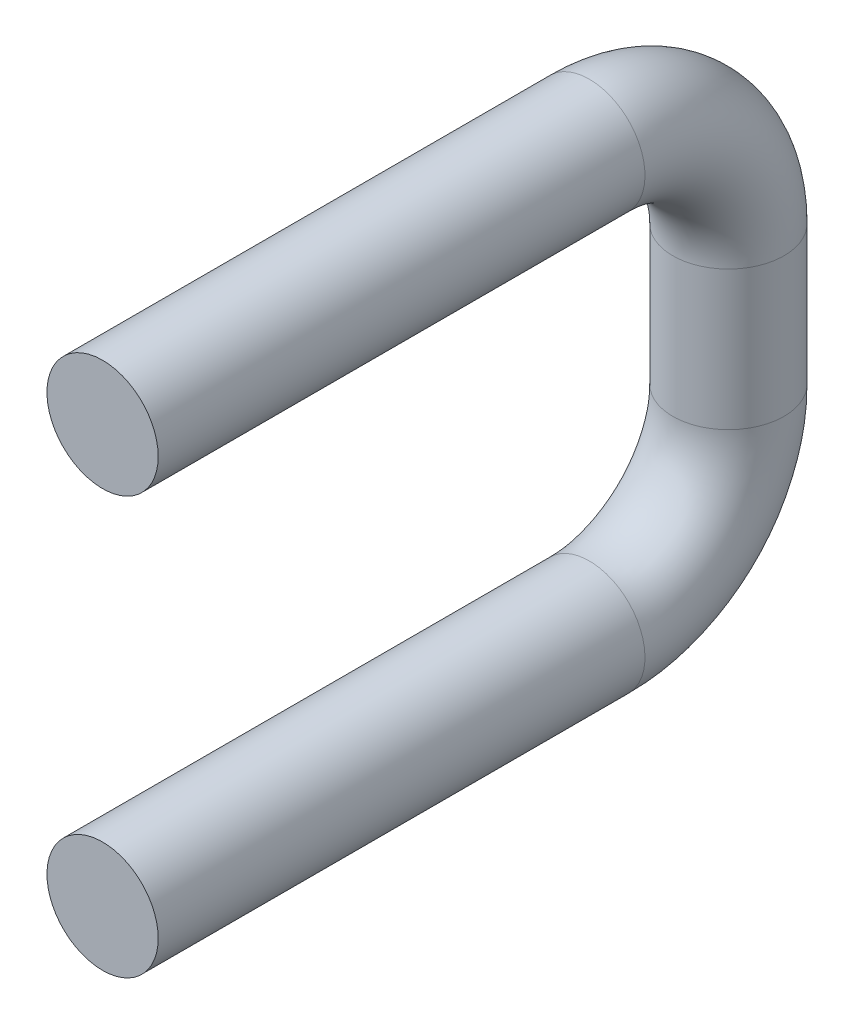
SolidWorks part; units mm, degrees
material "СТ3КП"
ref_plane "Спереди" through (0, 0, 0) normal (0, 0, 1) x (1, 0, 0)
ref_plane "Сверху" through (0, 0, 0) normal (0, 1, 0) x (1, 0, 0)
ref_plane "Справа" through (0, 0, 0) normal (1, 0, 0) x (0, 0, -1)
sketch "Эскиз1" plane through (0, 0, 0) normal (1, 0, 0) x (0, 0, -1)
  line L0 (-15, 15) -> (-15, -15) construction
  line L3 (0, -15) -> (35, -15)
  line L4 (45, 5) -> (45, -5)
  line L5 (-15, -15) -> (15, 15) construction
  line L6 (15, 15) -> (15, -15) construction
  line L7 (0, -1000) -> (0, 49000) construction
  line L8 (0, 15) -> (35, 15)
  arc A0 (35, 15) -> (45, 5) centre (35, 5) cw
  arc A1 (35, -15) -> (45, -5) centre (35, -5) ccw
  point P4 (45, 0)
  point P9 (0, 0)
  point P12 (15, 0)
  dimension "D4" = 10
  dimension "D1" = 30
  dimension "D2" = 30
  dimension "D3" = 30
sketch "Эскиз2" plane through (0, 0, 0) normal (0, 0, 1) x (1, 0, 0)
  line L0 (0, -15) -> (0, -5) construction
  line L1 (0, -201000) -> (0, 249000) construction
  circle A0 centre (0, -15) radius 4
  dimension "D1" = 8
sweep "По траектории1" add profiles "Эскиз2" path "Эскиз1"
mirror "Зеркальное отражение1" [suppressed]
equation "\"D3@Эскиз1\"=\"D1@Эскиз1\""
